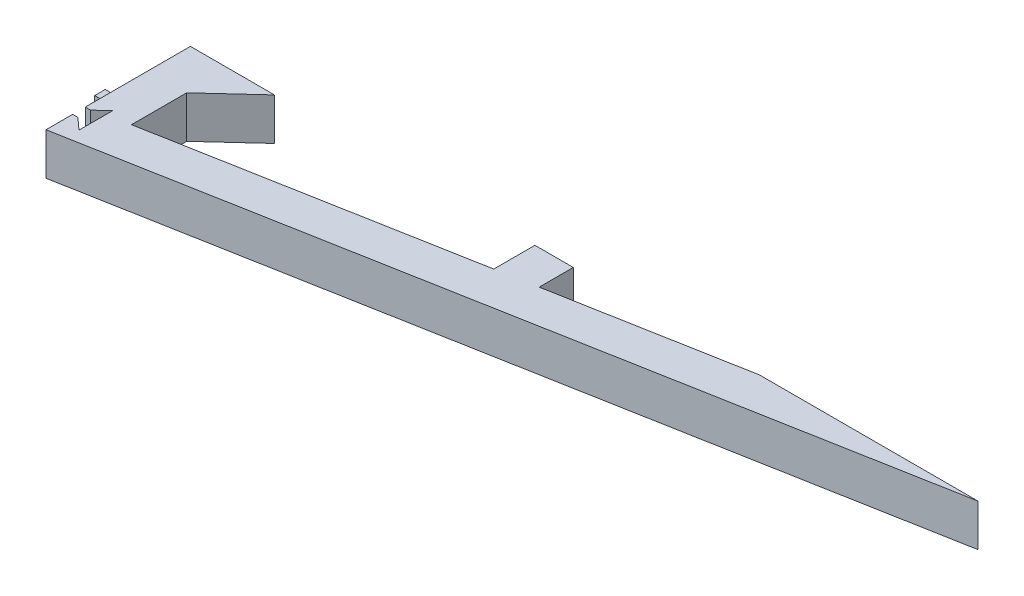
SolidWorks part; units mm, degrees
ref_plane "Přední rovina" through (0, 0, 0) normal (0, 0, 1) x (1, 0, 0)
ref_plane "Horní rovina" through (0, 0, 0) normal (0, 1, 0) x (1, 0, 0)
ref_plane "Pravá rovina" through (0, 0, 0) normal (1, 0, 0) x (0, 0, -1)
sketch "Skica1" plane through (0, 0, 0) normal (0, 1, 0) x (1, 0, 0)
  line L0 (0, 0) -> (0, -27.4721)
  line L1 (0, -27.4721) -> (149.85, 0.0008)
  line L7 (65.55, -7.8294) -> (7.3, -18.5088)
  line L8 (7.3, -18.5088) -> (7.3, 0)
  line L9 (7.3, 0) -> (0, 0)
  line L15 (65.55, -7.8294) -> (65.55, 0)
  line L16 (65.55, 0) -> (72.85, 0)
  line L17 (72.85, 0) -> (72.85, -6.4911)
  line L18 (72.85, -6.4911) -> (108.2597, 0.0008)
  line L19 (108.2597, 0.0008) -> (149.85, 0.0008)
  dimension "D1" = 27.4721
  dimension "D2" = 7.3
  dimension "D3" = 149.85
  dimension "D4" = 7.3
  dimension "D5" = 7.5
  dimension "D6" = 79.611
  dimension "D7" = 77
  dimension "D8" = 7.5
extrude "Přidat vysunutím1" add sketch "Skica1" along normal blind 8
sketch "Skica2" plane through (0, 8, 0) normal (0, 1, 0) x (1, 0, 0)
  line L6 (0, -20) -> (1, -20)
  line L7 (0, 0) -> (0, -27.4721) construction
  line L8 (1, -20) -> (3.2, -18)
  line L9 (3.2, -18) -> (3.2, -24.4)
  line L10 (3.2, -24.4) -> (1, -22.4)
  line L11 (1, -22.4) -> (0, -22.4)
  line L12 (0, -22.4) -> (0, -20)
  line L13 (7.3, 0) -> (0, 0) construction
  dimension "D1" = 1
  dimension "D2" = 1
  dimension "D3" = 3.2
  dimension "6,8" = 6.4
  dimension "2,8" = 2.4
  dimension "D4" = 2
  dimension "4" = 18
extrude "Odebrat vysunutím1" cut sketch "Skica2" against normal through all
sketch "Skica3" plane through (0, 0, 0) normal (-1, 0, 0) x (0, 0, 1)
  line L0 (0, 8) -> (0, 0) construction
  line L5 (12.2, 5) -> (14.2, 5)
  line L6 (12.2, 5) -> (12.2, 3)
  line L7 (12.2, 3) -> (14.2, 3)
  line L8 (14.2, 5) -> (14.2, 3)
  line L14 (0, 8) -> (20, 8) construction
  dimension "D1" = 12.2
  dimension "D3" = 2
  dimension "D4" = 2
  dimension "D9" = 3
extrude "Přidat vysunutím2" add sketch "Skica3" along normal blind 4
sketch "Skica5" plane through (0, 8, 0) normal (0, 1, 0) x (1, 0, 0)
  line L11 (0, 0) -> (16, 0)
  line L12 (0, 0) -> (0, -8)
  line L13 (0, -8) -> (16, -8)
  line L14 (16, 0) -> (16, -8)
  dimension "D1" = 16
  dimension "D2" = 8
extrude "Přidat vysunutím4" add sketch "Skica5" against normal blind 8
sketch "Skica7" plane through (0, 0, 0) normal (0, -1, 0) x (1, 0, 0)
  line L3 (7.3, 8) -> (16, 8)
  line L4 (16, 8) -> (16, 0)
  line L5 (16, 0) -> (7.3, 8)
extrude "Odebrat vysunutím3" cut sketch "Skica7" against normal through all
sketch "Skica8" plane through (0, 0, 0) normal (0, 0, -1) x (-1, 0, 0)
  line L0 (0, 8) -> (0, 0) construction
  line L1 (-16, 8) -> (0, 8) construction
  line L2 (-72.85, 0) -> (-65.55, 0) construction
  line L3 (-65.55, 8) -> (-65.55, 0) construction
  circle A0 centre (-3.65, 4) radius 2.2
  circle A1 centre (-69.2, 4) radius 2.2
  dimension "D1" = 4.4
  dimension "D2" = 4.4
  dimension "D3" = 3.65
  dimension "D4" = 4
  dimension "D5" = 4
  dimension "D6" = 3.65
extrude "Odebrat vysunutím4" cut sketch "Skica8" against normal blind 9.4
